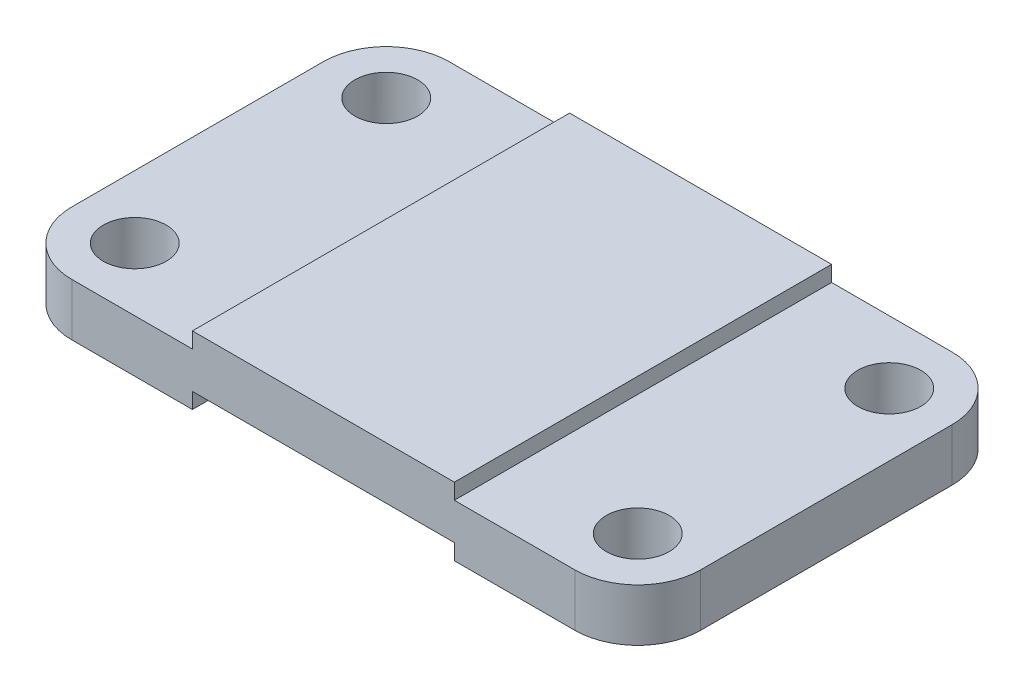
SolidWorks part; units mm, degrees
ref_plane "Front Plane" through (0, 0, 0) normal (0, 0, 1) x (1, 0, 0)
ref_plane "Top Plane" through (0, 0, 0) normal (0, 1, 0) x (1, 0, 0)
ref_plane "Right Plane" through (0, 0, 0) normal (1, 0, 0) x (0, 0, -1)
sketch "Sketch1" plane through (0, 0, 0) normal (0, 1, 0) x (1, 0, 0)
  line L0 (-68.1553, 0) -> (67.2816, 0) construction
  line L1 (0, -56.6505) -> (0, 61.0194) construction
  line L2 (-48, 36) -> (48, 36)
  line L3 (60, 24) -> (60, -24)
  line L4 (48, -36) -> (-48, -36)
  line L5 (-60, -24) -> (-60, 24)
  arc A0 (-48, -36) -> (-60, -24) centre (-48, -24) cw
  arc A1 (60, -24) -> (48, -36) centre (48, -24) cw
  arc A2 (48, 36) -> (60, 24) centre (48, 24) cw
  arc A3 (-48, 36) -> (-60, 24) centre (-48, 24) ccw
  point P13 (60, -36)
  point P16 (60, 36)
  point P19 (-60, 36)
  dimension "D3" = 12
  dimension "D1" = 120
  dimension "D2" = 72
extrude "Boss-Extrude1" add sketch "Sketch1" along normal blind 10
sketch "Sketch2" plane through (0, 10, 0) normal (0, 1, 0) x (1, 0, 0)
  line L0 (-25, -36) -> (25, -36)
  line L1 (-48, -36) -> (48, -36) construction
  line L2 (25, -36) -> (25, 36)
  line L3 (48, 36) -> (-48, 36) construction
  line L4 (25, 36) -> (-25, 36)
  line L5 (-25, 36) -> (-25, -36)
  line L6 (0, -45.0933) -> (0, 42.871) construction
  line L7 (-70.5566, 0) -> (67.964, 0) construction
  dimension "D1" = 35
extrude "Boss-Extrude2" add sketch "Sketch2" along normal blind 3
sketch "Sketch3" plane through (0, 0, 0) normal (0, -1, 0) x (1, 0, 0)
  line L0 (-25, 36) -> (25, 36)
  line L1 (-48, 36) -> (48, 36) construction
  line L2 (25, 36) -> (25, -36)
  line L3 (48, -36) -> (-48, -36) construction
  line L4 (25, -36) -> (-25, -36)
  line L5 (-25, -36) -> (-25, 36)
  line L6 (0, 43.9822) -> (0, -44.3525) construction
  dimension "D1" = 35
extrude "Cut-Extrude1" cut sketch "Sketch3" against normal blind 3
sketch "Sketch4" plane through (0, 10, 0) normal (0, 1, 0) x (1, 0, 0)
  circle A0 centre (48, 24) radius 6
  circle A1 centre (48, -24) radius 6
  circle A2 centre (-48, -24) radius 6
  circle A3 centre (-48, 24) radius 6
  dimension "D1" = 12
extrude "Cut-Extrude3" cut sketch "Sketch4" against normal blind 49
